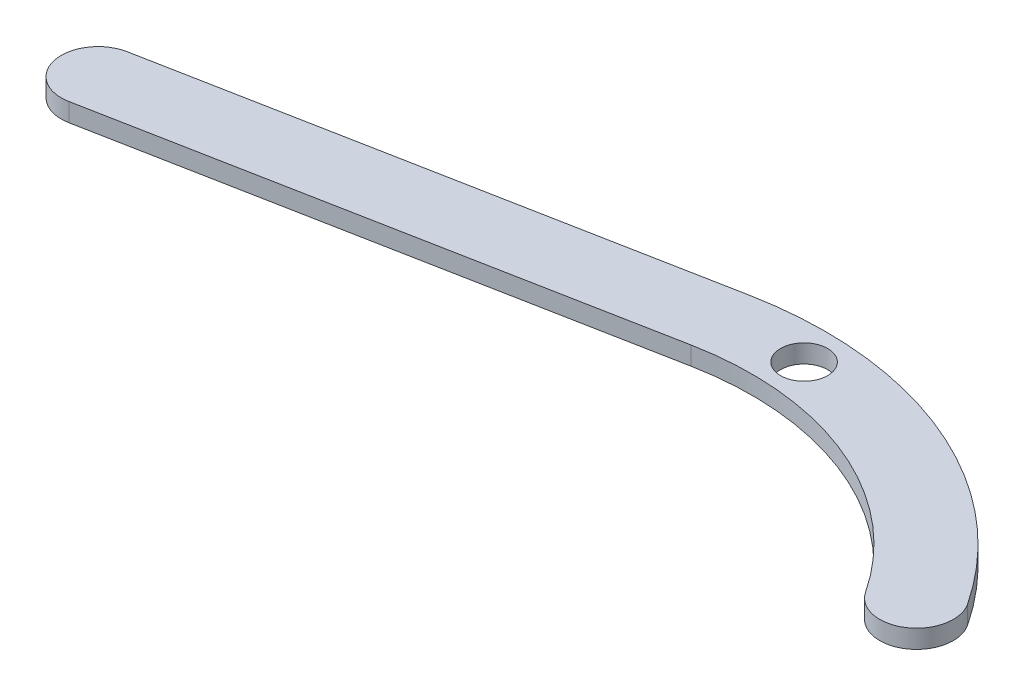
SolidWorks part; units mm, degrees
ref_plane "Front Plane" through (0, 0, 0) normal (0, 0, 1) x (1, 0, 0)
ref_plane "Top Plane" through (0, 0, 0) normal (0, 1, 0) x (1, 0, 0)
ref_plane "Right Plane" through (0, 0, 0) normal (1, 0, 0) x (0, 0, -1)
sketch "Sketch2" plane through (0, 0, 0) normal (0, 1, 0) x (1, 0, 0)
  line L4 (44.5362, 1.425) -> (-0.5126, -7.2256)
  line L5 (0.6849, -13.4617) -> (45.7337, -4.8111)
  arc A3 (-0.5126, -7.2256) -> (0.6849, -13.4617) centre (0.0862, -10.3436) ccw
  arc A4 (71.7171, -15.7555) -> (45.7337, -4.8111) centre (50.5236, -29.7554) ccw
  arc A5 (77.0154, -12.2555) -> (44.5362, 1.425) centre (50.5236, -29.7554) ccw
  arc A6 (71.7171, -15.7555) -> (77.0154, -12.2555) centre (74.3663, -14.0055) ccw
  point P1 (71.2953, -8.4658)
  point P2 (74.3663, -13.4617)
  dimension "D1" = 50.8
  dimension "D2" = 63.5
  dimension "D3" = 6.35
  dimension "D4" = 44.45
extrude "Boss-Extrude1" add sketch "Sketch2" along normal blind 1.5875
sketch "Sketch3" plane through (0, 1.5875, 0) normal (0, 1, 0) x (1, 0, 0)
  line L0 (51.8712, -1.2126) -> (51.8712, 1.966) construction
  line L1 (51.8712, -1.2126) -> (51.8712, -4.3911) construction
  circle A0 centre (51.8712, -1.2126) radius 2.032
  arc A1 (77.0154, -12.2555) -> (44.5362, 1.425) centre (50.5236, -29.7554) ccw construction
  arc A2 (71.7171, -15.7555) -> (45.7337, -4.8111) centre (50.5236, -29.7554) ccw construction
  dimension "D1" = 4.064
extrude "Cut-Extrude1" cut sketch "Sketch3" against normal through all
